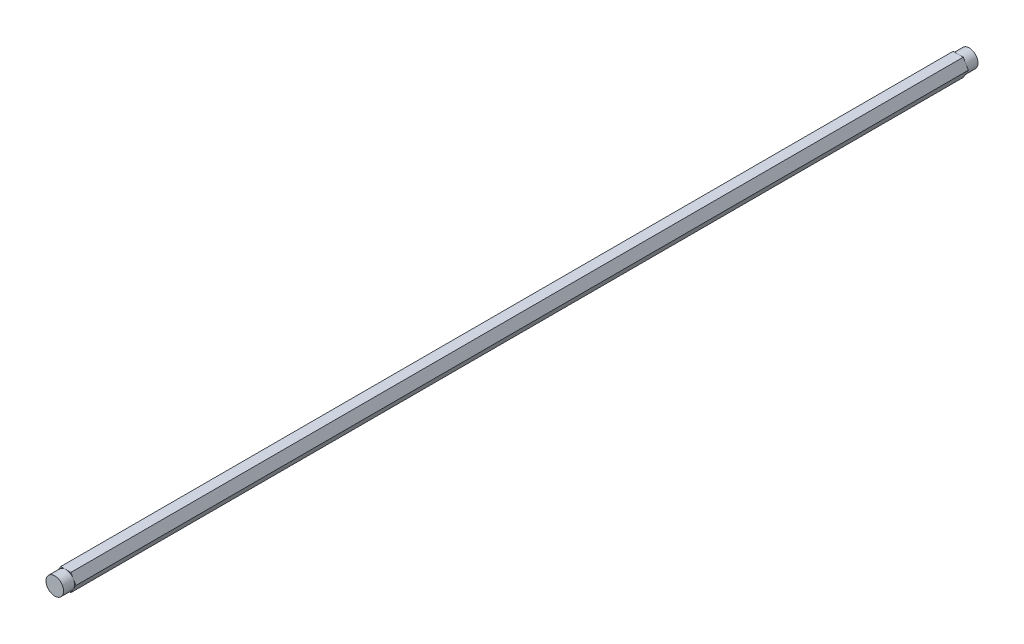
SolidWorks part; units mm, degrees
ref_plane "Front Plane" through (0, 0, 0) normal (0, 0, 1) x (1, 0, 0)
ref_plane "Top Plane" through (0, 0, 0) normal (0, 1, 0) x (1, 0, 0)
ref_plane "Right Plane" through (0, 0, 0) normal (1, 0, 0) x (0, 0, -1)
sketch "Sketch1" plane through (0, 0, 0) normal (0, 0, 1) x (1, 0, 0)
  line L1 (7.3323, 0) -> (3.6662, 6.35)
  line L2 (3.6662, 6.35) -> (-3.6662, 6.35)
  line L3 (-3.6662, 6.35) -> (-7.3323, 0)
  line L4 (-7.3323, 0) -> (-3.6662, -6.35)
  line L5 (-3.6662, -6.35) -> (3.6662, -6.35)
  line L6 (3.6662, -6.35) -> (7.3323, 0)
  circle A0 centre (0, 0) radius 6.35 construction
  dimension "D1" = 12.7
extrude "Boss-Extrude1" add sketch "Sketch1" along normal mid plane 660.4
sketch "Sketch4" plane through (0, 0, 330.2) normal (0, 0, 1) x (1, 0, 0)
  circle A0 centre (0, 0) radius 6.35
extrude "Cut-Extrude2" cut sketch "Sketch4" against normal blind 7.9502 flip side to cut
mirror "Mirror1" about plane through (0, 0, 0) normal (0, 0, 1) of "Cut-Extrude2"
